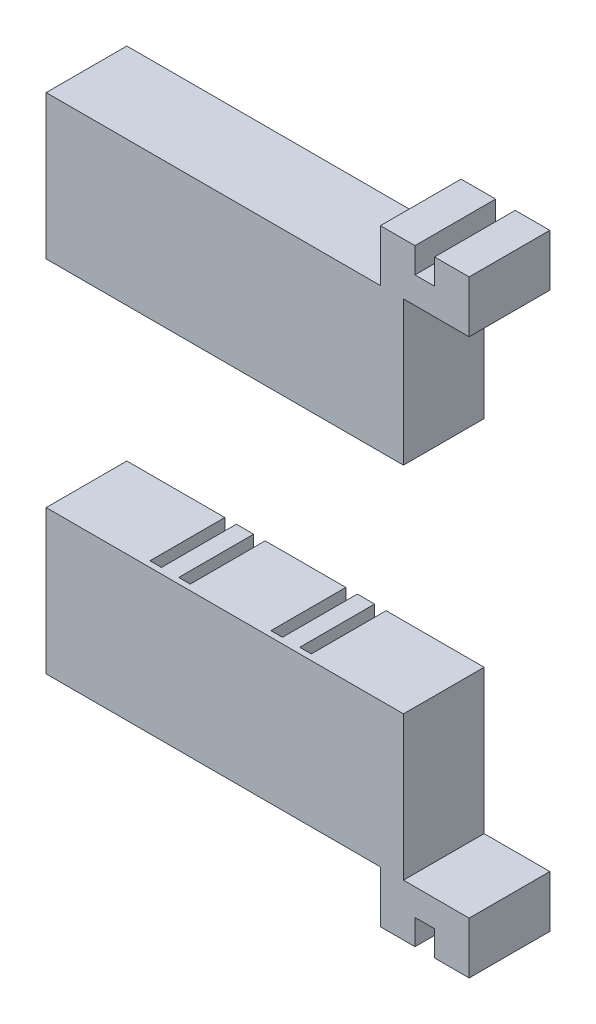
SolidWorks part; units mm, degrees
ref_plane "Front Plane" through (0, 0, 0) normal (0, 0, 1) x (1, 0, 0)
ref_plane "Top Plane" through (0, 0, 0) normal (0, 1, 0) x (1, 0, 0)
ref_plane "Right Plane" through (0, 0, 0) normal (1, 0, 0) x (0, 0, -1)
sketch "Sketch1" plane through (0, 0, 0) normal (0, 0, 1) x (1, 0, 0)
  line L0 (31, 0) -> (31, -25) construction
  line L1 (0, 0) -> (58, 0)
  line L2 (0, 0) -> (0, -25)
  line L3 (0, -25) -> (17, -25)
  line L4 (62, 0) -> (62, -25)
  line L5 (38, -25) -> (38, -12)
  line L6 (40, -10) -> (50, -10)
  line L7 (52, -12) -> (52, -16)
  line L8 (50, -18) -> (47, -18)
  line L9 (45, -20) -> (45, -25)
  line L10 (40, -25) -> (40, -13)
  line L11 (41, -12) -> (49, -12)
  line L12 (50, -13) -> (50, -15)
  line L13 (49, -16) -> (47, -16)
  line L14 (43, -20) -> (43, -25)
  line L15 (40, -25) -> (43, -25)
  line L16 (45, -25) -> (62, -25)
  line L17 (24, -25) -> (24, -12)
  line L18 (22, -10) -> (12, -10)
  line L19 (10, -12) -> (10, -16)
  line L20 (12, -18) -> (15, -18)
  line L21 (17, -20) -> (17, -25)
  line L22 (22, -13) -> (22, -25)
  line L23 (21, -12) -> (13, -12)
  line L24 (12, -13) -> (12, -15)
  line L25 (13, -16) -> (15, -16)
  line L26 (19, -20) -> (19, -25)
  line L27 (19, -25) -> (22, -25)
  line L28 (24, -25) -> (38, -25)
  line L29 (58, 0) -> (58, 9)
  line L30 (58, 9) -> (64, 9)
  line L31 (64, 9) -> (64, 4.6)
  line L32 (64, 4.6) -> (67.4, 4.6)
  line L33 (67.4, 4.6) -> (67.4, 9)
  line L34 (67.4, 9) -> (73.4, 9)
  line L35 (73.4, 9) -> (73.4, 0)
  line L36 (73.4, 0) -> (62, 0)
  line L37 (0, -87.365) -> (58, -87.365)
  line L38 (-15.2596, -49.6779) -> (119.0196, -49.6779) construction
  line L40 (0, -62.365) -> (0, -87.365)
  line L41 (58, -87.365) -> (58, -96.365)
  line L45 (73.4, -96.365) -> (73.4, -87.365)
  line L46 (0, -62.365) -> (17, -62.365)
  line L47 (62, -62.365) -> (62, -87.365)
  line L48 (62, -87.365) -> (73.4, -87.365)
  line L49 (17, -67.365) -> (17, -62.365)
  line L50 (15, -69.365) -> (12, -69.365)
  line L51 (10, -71.365) -> (10, -75.365)
  line L52 (12, -77.365) -> (22, -77.365)
  line L53 (24, -75.365) -> (24, -62.365)
  line L54 (38, -62.365) -> (38, -75.365)
  line L55 (40, -77.365) -> (50, -77.365)
  line L56 (52, -75.365) -> (52, -71.365)
  line L57 (50, -69.365) -> (47, -69.365)
  line L58 (45, -67.365) -> (45, -62.365)
  line L59 (22, -62.365) -> (22, -74.365)
  line L60 (21, -75.365) -> (13, -75.365)
  line L61 (12, -74.365) -> (12, -72.365)
  line L62 (13, -71.365) -> (15, -71.365)
  line L63 (19, -67.365) -> (19, -62.365)
  line L64 (40, -62.365) -> (40, -74.365)
  line L65 (41, -75.365) -> (49, -75.365)
  line L66 (50, -74.365) -> (50, -72.365)
  line L67 (49, -71.365) -> (47, -71.365)
  line L68 (43, -67.365) -> (43, -62.365)
  line L69 (19, -62.365) -> (22, -62.365)
  line L70 (24, -62.365) -> (38, -62.365)
  line L71 (40, -62.365) -> (43, -62.365)
  line L72 (45, -62.365) -> (62, -62.365)
  line L73 (58, -96.365) -> (64, -96.365)
  line L74 (64, -96.365) -> (64, -91.965)
  line L75 (64, -91.965) -> (67.4, -91.965)
  line L76 (67.4, -91.965) -> (67.4, -96.365)
  line L77 (67.4, -96.365) -> (73.4, -96.365)
  arc A0 (40, -10) -> (38, -12) centre (40, -12) ccw
  arc A1 (47, -18) -> (45, -20) centre (47, -20) ccw
  arc A2 (52, -16) -> (50, -18) centre (50, -16) cw
  arc A3 (52, -12) -> (50, -10) centre (50, -12) ccw
  arc A4 (50, -15) -> (49, -16) centre (49, -15) cw
  arc A5 (49, -12) -> (50, -13) centre (49, -13) cw
  arc A6 (41, -12) -> (40, -13) centre (41, -13) ccw
  arc A7 (43, -20) -> (47, -16) centre (47, -20) cw
  arc A8 (17, -20) -> (15, -18) centre (15, -20) ccw
  arc A9 (12, -18) -> (10, -16) centre (12, -16) cw
  arc A10 (10, -12) -> (12, -10) centre (12, -12) cw
  arc A11 (24, -12) -> (22, -10) centre (22, -12) ccw
  arc A12 (12, -15) -> (13, -16) centre (13, -15) ccw
  arc A13 (13, -12) -> (12, -13) centre (13, -13) ccw
  arc A14 (22, -13) -> (21, -12) centre (21, -13) ccw
  arc A15 (15, -16) -> (19, -20) centre (15, -20) cw
  arc A16 (38, -75.365) -> (40, -77.365) centre (40, -75.365) ccw
  arc A17 (52, -75.365) -> (50, -77.365) centre (50, -75.365) cw
  arc A18 (52, -71.365) -> (50, -69.365) centre (50, -71.365) ccw
  arc A19 (47, -69.365) -> (45, -67.365) centre (47, -67.365) cw
  arc A20 (15, -69.365) -> (17, -67.365) centre (15, -67.365) ccw
  arc A21 (12, -69.365) -> (10, -71.365) centre (12, -71.365) ccw
  arc A22 (12, -77.365) -> (10, -75.365) centre (12, -75.365) cw
  arc A23 (22, -77.365) -> (24, -75.365) centre (22, -75.365) ccw
  arc A24 (41, -75.365) -> (40, -74.365) centre (41, -74.365) cw
  arc A25 (50, -74.365) -> (49, -75.365) centre (49, -74.365) cw
  arc A26 (50, -72.365) -> (49, -71.365) centre (49, -72.365) ccw
  arc A27 (13, -71.365) -> (12, -72.365) centre (13, -72.365) ccw
  arc A28 (13, -75.365) -> (12, -74.365) centre (13, -74.365) cw
  arc A29 (22, -74.365) -> (21, -75.365) centre (21, -74.365) cw
  arc A30 (19, -67.365) -> (15, -71.365) centre (15, -67.365) cw
  arc A31 (47, -71.365) -> (43, -67.365) centre (47, -67.365) cw
  point P15 (38, -10)
  point P18 (45, -18)
  point P21 (52, -18)
  point P24 (52, -10)
  point P47 (17, -18)
  point P50 (10, -18)
  point P53 (10, -10)
  point P56 (24, -10)
  point P102 (38, -77.365)
  point P106 (52, -77.365)
  point P109 (52, -69.365)
  point P116 (10, -69.365)
  point P119 (10, -77.365)
  point P122 (24, -77.365)
  dimension "D8" = 2
  dimension "D9" = 2
  dimension "D11" = 1
  dimension "D12" = 4
  dimension "D18" = 2
  dimension "D20" = 1
  dimension "D21" = 4
  dimension "D35" = 2
  dimension "D36" = 1
  dimension "D37" = 4
  dimension "D39" = 4
  dimension "D1" = 62
  dimension "D2" = 25
  dimension "D3" = 31
  dimension "D4" = 15
  dimension "D5" = 14
  dimension "D6" = 8
  dimension "D7" = 7
  dimension "D10" = 2
  dimension "D13" = 7
  dimension "D14" = 14
  dimension "D15" = 8
  dimension "D16" = 7
  dimension "D17" = 15
  dimension "D19" = 2
  dimension "D22" = 9
  dimension "D23" = 6
  dimension "D24" = 3.4
  dimension "D25" = 6
  dimension "D26" = 4
  dimension "D27" = 4.4
  dimension "D28" = 4.4
  dimension "D29" = 7
  dimension "D30" = 25
  dimension "D31" = 15
  dimension "D32" = 15
  dimension "D33" = 8
  dimension "D34" = 8
  dimension "D38" = 2
  dimension "D40" = 9
  dimension "D41" = 9
  dimension "D42" = 6
  dimension "D43" = 6
  dimension "D44" = 3.4
  dimension "D45" = 4.4
  dimension "D46" = 4.4
extrude "Boss-Extrude1" add sketch "Sketch1" along normal blind 13
sketch "Sketch7" plane through (0, 0, 13) normal (0, 0, 1) x (1, 0, 0)
  line L0 (0, 0) -> (58, 0)
  line L1 (58, 0) -> (58, 9)
  line L2 (58, 9) -> (64, 9)
  line L3 (64, 9) -> (64, 4.6)
  line L4 (64, 4.6) -> (67.4, 4.6)
  line L5 (67.4, 4.6) -> (67.4, 9)
  line L6 (67.4, 9) -> (73.4, 9)
  line L7 (73.4, 9) -> (73.4, 0)
  line L8 (73.4, 0) -> (62, 0)
  line L9 (62, 0) -> (62, -25)
  line L10 (62, -25) -> (0, -25)
  line L11 (0, -25) -> (0, 0)
  line L12 (0, -62.365) -> (62, -62.365)
  line L13 (62, -62.365) -> (62, -87.365)
  line L14 (62, -87.365) -> (73.4, -87.365)
  line L15 (73.4, -87.365) -> (73.4, -96.365)
  line L16 (73.4, -96.365) -> (67.4, -96.365)
  line L17 (67.4, -96.365) -> (67.4, -91.965)
  line L18 (67.4, -91.965) -> (64, -91.965)
  line L19 (64, -91.965) -> (64, -96.365)
  line L20 (64, -96.365) -> (58, -96.365)
  line L21 (58, -96.365) -> (58, -87.365)
  line L22 (58, -87.365) -> (0, -87.365)
  line L23 (0, -87.365) -> (0, -62.365)
extrude "Boss-Extrude3" add sketch "Sketch7" along normal blind 1
sketch "Sketch9" plane through (58, 0, 0) normal (-1, 0, 0) x (0, 0, 1)
  text T0 "29"
extrude "Cut-Extrude1" cut sketch "Sketch9" against normal blind 1
sketch "Sketch10" plane through (58, 0, 0) normal (-1, 0, 0) x (0, 0, 1)
  text T0 "29"
extrude "Cut-Extrude2" cut sketch "Sketch10" against normal blind 1
